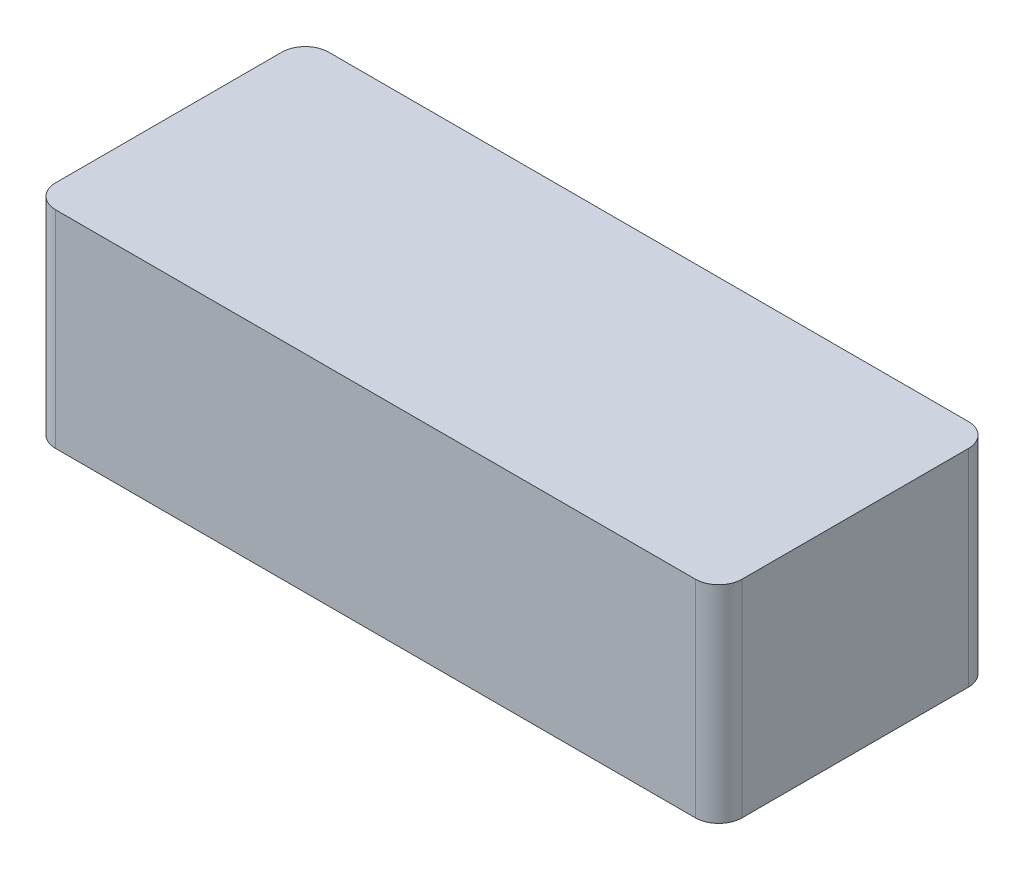
SolidWorks part; units mm, degrees
material "ABS"
ref_plane "Front Plane" through (0, 0, 0) normal (0, 0, 1) x (1, 0, 0)
ref_plane "Top Plane" through (0, 0, 0) normal (0, 1, 0) x (1, 0, 0)
ref_plane "Right Plane" through (0, 0, 0) normal (1, 0, 0) x (0, 0, -1)
sketch "SK_1" plane through (0, 0, 0) normal (0, 1, 0) x (1, 0, 0)
  line L1 (-41, -17.5) -> (41, -17.5)
  line L2 (-44, -14.5) -> (-44, 14.5)
  line L3 (-41, 17.5) -> (41, 17.5)
  line L4 (44, -14.5) -> (44, 14.5)
  line L5 (-44, -17.5) -> (44, 17.5) construction
  line L6 (-44, 17.5) -> (44, -17.5) construction
  arc A0 (41, -17.5) -> (44, -14.5) centre (41, -14.5) ccw
  arc A1 (-44, 14.5) -> (-41, 17.5) centre (-41, 14.5) cw
  arc A2 (-41, -17.5) -> (-44, -14.5) centre (-41, -14.5) cw
  arc A3 (41, 17.5) -> (44, 14.5) centre (41, 14.5) cw
  point P0 (0, 0)
  dimension "D1" = 3
  dimension "W1" = 88
  dimension "H1" = 35
  dimension "X1" = 44
  dimension "Y1" = 17.5
extrude "Cell_Pack" add sketch "SK_1" along normal blind 26.5
sketch "SK_2" plane through (0, 0, 0) normal (0, 1, 0) x (1, 0, 0)
  line L1 (-51, -6) -> (-45, -6)
  line L2 (-52, -5) -> (-52, 5)
  line L3 (-51, 6) -> (-45, 6)
  line L4 (-44, -5) -> (-44, 5)
  line L5 (-52, -6) -> (-44, 6) construction
  line L6 (-52, 6) -> (-44, -6) construction
  arc A0 (-45, -6) -> (-44, -5) centre (-45, -5) ccw
  arc A1 (-52, 5) -> (-51, 6) centre (-51, 5) cw
  arc A2 (-51, -6) -> (-52, -5) centre (-51, -5) cw
  arc A3 (-45, 6) -> (-44, 5) centre (-45, 5) cw
  point P0 (-48, 0)
  dimension "D1" = 1
  dimension "W1" = 8
  dimension "H1" = 12
  dimension "X1" = 52
  dimension "Y1" = 6
extrude "Connector" add sketch "SK_2" along normal blind 10 from offset 8
equation "\"Bat_L\" = 88 'length"
equation "\"Bat_W\" = 35 'width"
equation "\"Bat_H\" = 26.5 'height"
equation "\"W1@SK_1\" = \"Bat_L\""
equation "\"H1@SK_1\" = \"Bat_W\""
equation "\"X1@SK_1\" = -((0)-(\"Bat_L\")/2)"
equation "\"Y1@SK_1\" = -((0)-(\"Bat_W\")/2)"
equation "\"D1@Cell_Pack\" = (\"Bat_H\")-(0)"
equation "\"X1@SK_2\" = -((-\"Bat_L\"/2 - 4)-(8)/2)"
